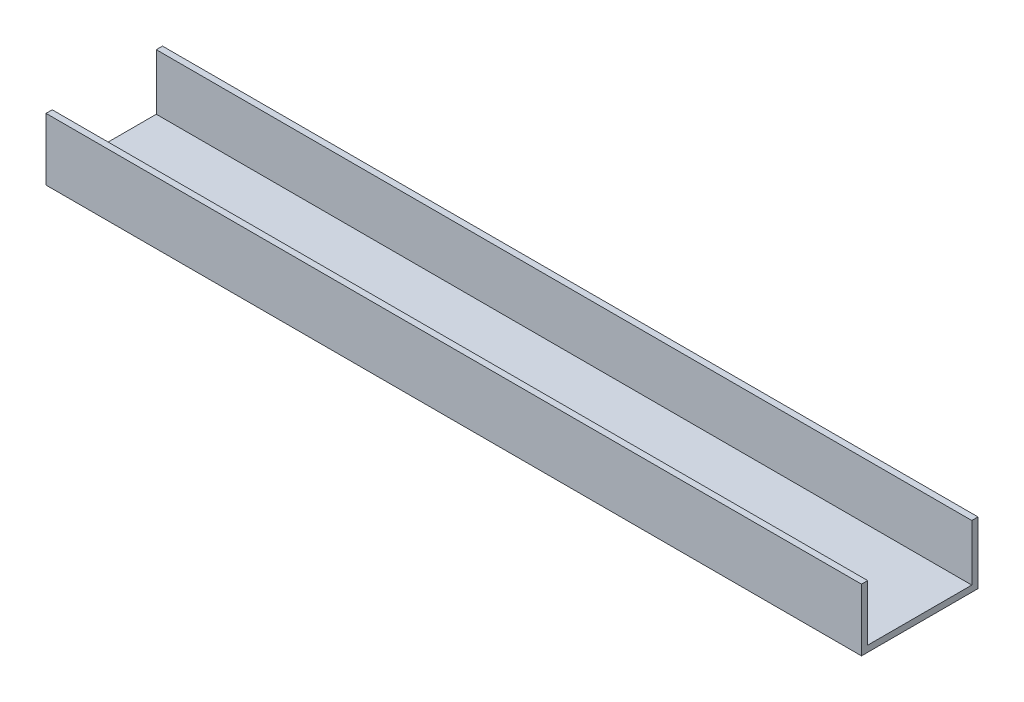
SolidWorks part; units mm, degrees
ref_plane "정면" through (0, 0, 0) normal (0, 0, 1) x (1, 0, 0)
ref_plane "윗면" through (0, 0, 0) normal (0, 1, 0) x (1, 0, 0)
ref_plane "우측면" through (0, 0, 0) normal (1, 0, 0) x (0, 0, -1)
sketch "스케치1" plane through (0, 0, 0) normal (0, 1, 0) x (1, 0, 0)
  line L1 (0, 0) -> (525, 0)
  line L2 (0, 0) -> (0, 75)
  line L3 (0, 75) -> (525, 75)
  line L4 (525, 0) -> (525, 75)
  dimension "D1" = 525
  dimension "D2" = 75
extrude "보스-돌출1" add sketch "스케치1" along normal blind 4
sketch "스케치2" plane through (0, 4, 0) normal (0, 1, 0) x (1, 0, 0)
  line L0 (525, 0) -> (525, 75) construction
  line L1 (0, 75) -> (525, 75)
  line L2 (0, 75) -> (0, 71)
  line L3 (0, 71) -> (525, 71)
  line L4 (525, 75) -> (525, 71)
  line L5 (0, 75) -> (0, 0) construction
  line L6 (525, 0) -> (0, 0)
  line L7 (525, 0) -> (525, 4)
  line L8 (525, 4) -> (0, 4)
  line L9 (0, 0) -> (0, 4)
  dimension "D1" = 4
  dimension "D2" = 4
extrude "보스-돌출2" add sketch "스케치2" along normal blind 36
